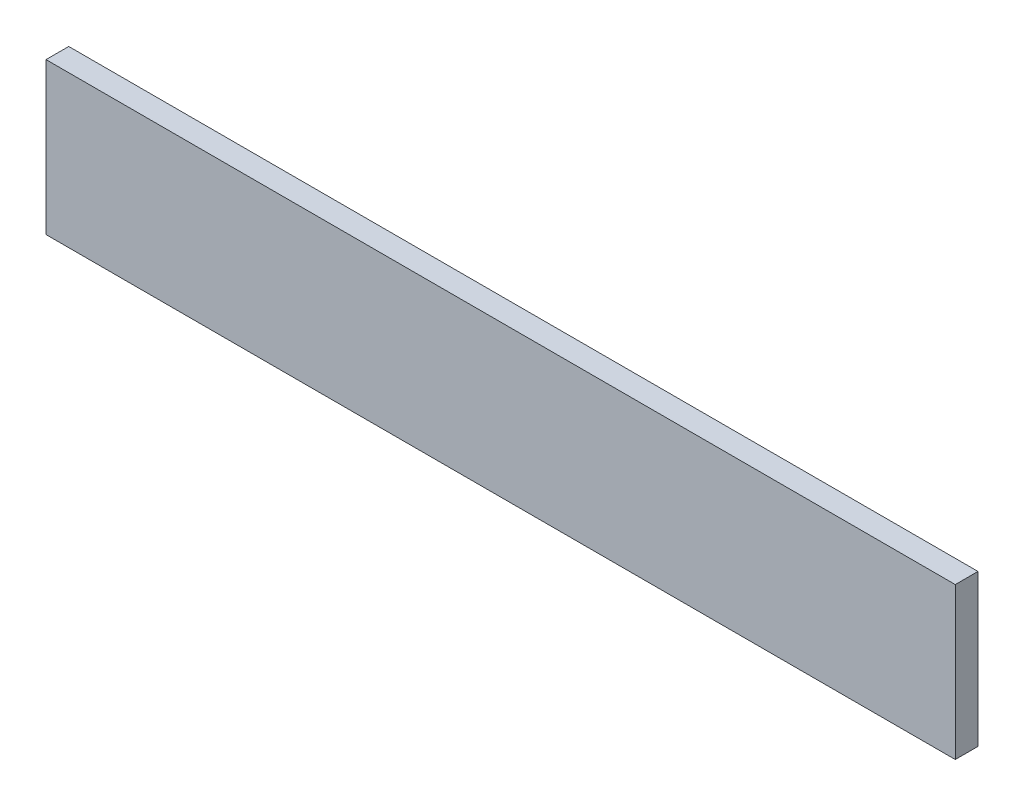
SolidWorks part; units mm, degrees
ref_plane "Plan de face" through (0, 0, 0) normal (0, 0, 1) x (1, 0, 0)
ref_plane "Plan de dessus" through (0, 0, 0) normal (0, 1, 0) x (1, 0, 0)
ref_plane "Plan de droite" through (0, 0, 0) normal (1, 0, 0) x (0, 0, -1)
sketch "Esquisse1" plane through (0, 0, 0) normal (0, 0, 1) x (1, 0, 0)
  line L1 (0, 0) -> (-240, 0)
  line L2 (0, 0) -> (0, 40)
  line L3 (0, 40) -> (-240, 40)
  line L4 (-240, 0) -> (-240, 40)
  dimension "D1" = 40
  dimension "D2" = 240
extrude "Boss.-Extru.1" add sketch "Esquisse1" along normal blind 6
